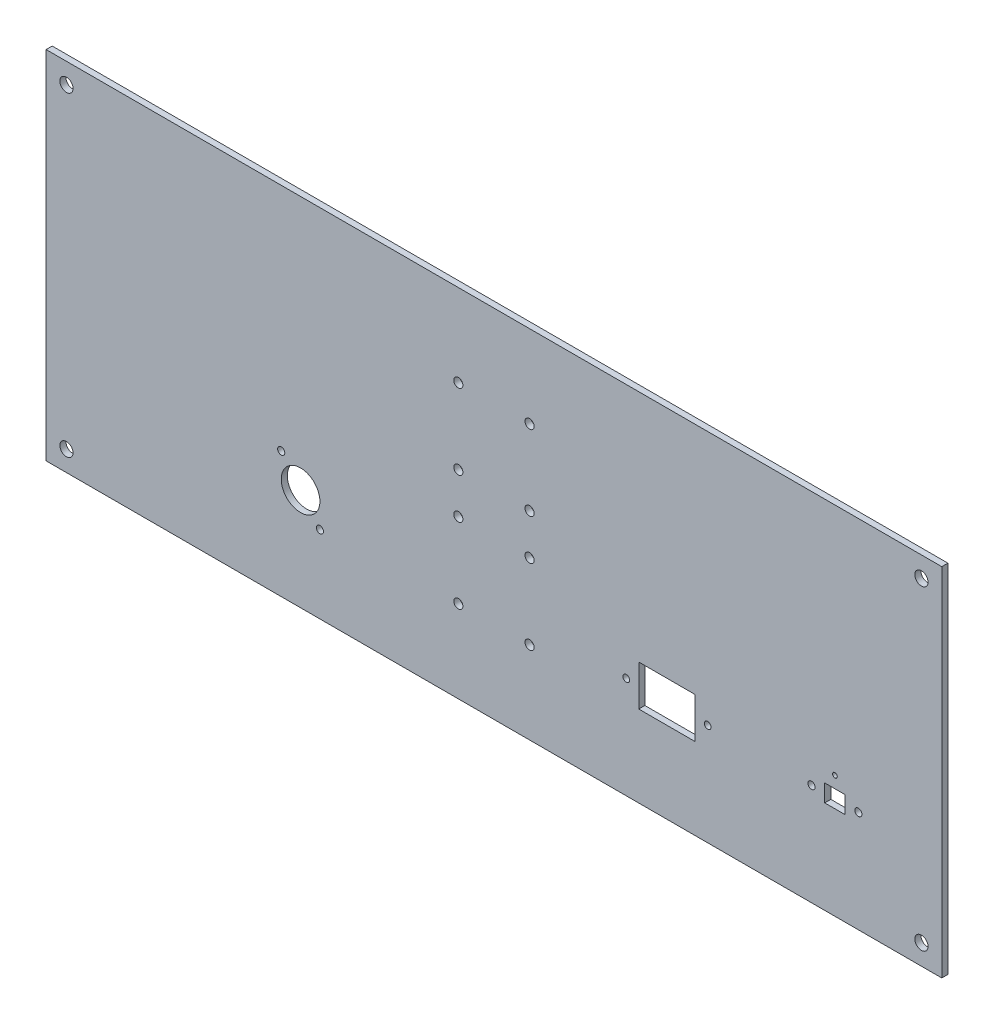
SolidWorks part; units mm, degrees
ref_plane "Front Plane" through (0, 0, 0) normal (0, 0, 1) x (1, 0, 0)
ref_plane "Top Plane" through (0, 0, 0) normal (0, 1, 0) x (1, 0, 0)
ref_plane "Right Plane" through (0, 0, 0) normal (1, 0, 0) x (0, 0, -1)
sketch "Sketch1" plane through (0, 0, 0) normal (0, 0, 1) x (1, 0, 0)
  line L0 (20, 155) -> (420, 155) construction
  line L1 (0, 0) -> (440, 0)
  line L2 (0, 0) -> (0, 175)
  line L3 (0, 175) -> (440, 175)
  line L4 (440, 0) -> (440, 175)
  line L5 (355, 155) -> (355, 20) construction
  line L6 (95, 155) -> (95, 20) construction
  line L7 (420, 20) -> (420, 155) construction
  line L8 (20, 20) -> (420, 20) construction
  line L9 (20, 20) -> (20, 155) construction
  line L10 (75, 155) -> (75, 20) construction
  line L11 (335, 155) -> (335, 20) construction
  line L12 (125, 155) -> (125, 20) construction
  line L13 (95, 50) -> (335, 50) construction
  line L14 (305, 155) -> (305, 20) construction
  line L15 (387.5, 20) -> (387.5, 155) construction
  line L16 (291.15, 40) -> (318.85, 40)
  line L17 (291.15, 40) -> (291.15, 60)
  line L18 (291.15, 60) -> (318.85, 60)
  line L19 (318.85, 40) -> (318.85, 60)
  line L20 (291.15, 40) -> (318.85, 60) construction
  line L21 (291.15, 60) -> (318.85, 40) construction
  line L22 (382.5, 45.75) -> (392.5, 45.75)
  line L23 (382.5, 45.75) -> (382.5, 54.25)
  line L24 (382.5, 54.25) -> (392.5, 54.25)
  line L25 (392.5, 45.75) -> (392.5, 54.25)
  line L26 (382.5, 45.75) -> (392.5, 54.25) construction
  line L27 (382.5, 54.25) -> (392.5, 45.75) construction
  line L28 (335, 50) -> (420, 50) construction
  line L29 (220, 20) -> (220, 155) construction
  line L30 (202.5, 155) -> (202.5, 20) construction
  line L31 (237.5, 155) -> (237.5, 20) construction
  line L32 (125, 87.5) -> (305, 87.5) construction
  circle A0 centre (125, 50) radius 9.5
  circle A1 centre (115.5, 62) radius 1.75
  circle A2 centre (134.5, 38) radius 1.75
  circle A3 centre (285, 50) radius 1.65
  circle A4 centre (325, 50) radius 1.65
  circle A5 centre (387.5, 60) radius 1.15
  circle A6 centre (376, 50) radius 1.75
  circle A7 centre (399, 50) radius 1.75
  circle A8 centre (10, 165) radius 3.25
  circle A9 centre (10, 10) radius 3.25
  circle A10 centre (430, 10) radius 3.25
  circle A11 centre (430, 165) radius 3.25
  circle A12 centre (202.5, 134.5) radius 2.25
  circle A13 centre (202.5, 97.5) radius 2.25
  circle A14 centre (237.5, 134.5) radius 2.25
  circle A15 centre (237.5, 97.5) radius 2.25
  circle A16 centre (237.5, 77.5) radius 2.25
  circle A17 centre (237.5, 40.5) radius 2.25
  circle A18 centre (202.5, 77.5) radius 2.25
  circle A19 centre (202.5, 40.5) radius 2.25
  point P24 (305, 50)
  point P37 (387.5, 50)
  dimension "D9" = 30
  dimension "D13" = 20
  dimension "D12" = 20
  dimension "D14" = 3.3
  dimension "D15" = 3.3
  dimension "D20" = 5.75
  dimension "D21" = 2.3
  dimension "D22" = 23
  dimension "D23" = 11.5
  dimension "D24" = 3.5
  dimension "D25" = 3.5
  dimension "D30" = 6.5
  dimension "D33" = 10
  dimension "D51" = 3.5
  dimension "D52" = 19
  dimension "D54" = 4.5
  dimension "D59" = 37
  dimension "D1" = 55
  dimension "D2" = 65
  dimension "D3" = 440
  dimension "D4" = 20
  dimension "D5" = 20
  dimension "D6" = 240
  dimension "D7" = 30
  dimension "D8" = 30
  dimension "D10" = 20
  dimension "D11" = 27.7
  dimension "D16" = 8.5
  dimension "D17" = 10
  dimension "D18" = 32.5
  dimension "D19" = 32.5
  dimension "D26" = 50
  dimension "D27" = 125
  dimension "D28" = 135
  dimension "D29" = 52.5
  dimension "D31" = 10
  dimension "D32" = 10
  dimension "D34" = 10
  dimension "D35" = 10
  dimension "D36" = 10
  dimension "D37" = 10
  dimension "D38" = 10
  dimension "D39" = 12
  dimension "D40" = 12
  dimension "D41" = 9.5
  dimension "D42" = 9.5
  dimension "D43" = 38
  dimension "D44" = 62
  dimension "D45" = 134.5
  dimension "D46" = 115.5
  dimension "D47" = 10
  dimension "D48" = 4.25
  dimension "D49" = 13.85
  dimension "D50" = 10
  dimension "D53" = 220
  dimension "D55" = 17.5
  dimension "D56" = 35
  dimension "D57" = 87.5
  dimension "D58" = 175
  dimension "D60" = 37
  dimension "D61" = 10
  dimension "D62" = 10
  dimension "D63" = 10
  dimension "D64" = 10
  dimension "D65" = 37
  dimension "D66" = 37
  dimension "D67" = 40.5
  dimension "D68" = 77.5
  dimension "D69" = 97.5
  dimension "D70" = 134.5
  dimension "D71" = 202.5
  dimension "D72" = 237.5
extrude "Boss-Extrude1" add sketch "Sketch1" along normal blind 3
